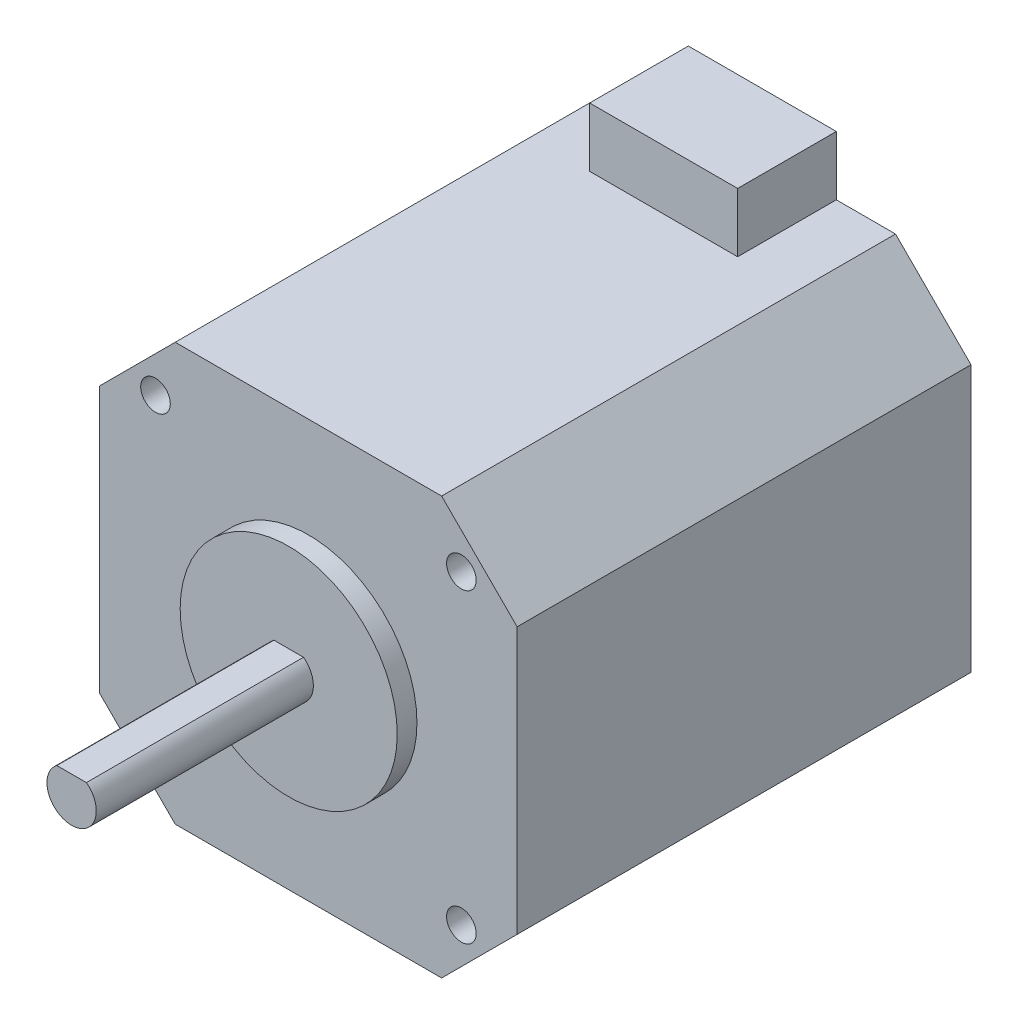
SolidWorks part; units mm, degrees
ref_plane "Front Plane" through (0, 0, 0) normal (0, 0, 1) x (1, 0, 0)
ref_plane "Top Plane" through (0, 0, 0) normal (0, 1, 0) x (1, 0, 0)
ref_plane "Right Plane" through (0, 0, 0) normal (1, 0, 0) x (0, 0, -1)
sketch "Sketch1" plane through (0, 0, 0) normal (0, 0, 1) x (1, 0, 0)
  line L0 (7.65, 0) -> (0, 7.65)
  line L1 (0, 7.65) -> (0, 34.65)
  line L2 (0, 34.65) -> (7.65, 42.3)
  line L3 (7.65, 42.3) -> (34.65, 42.3)
  line L4 (34.65, 42.3) -> (42.3, 34.65)
  line L5 (42.3, 34.65) -> (42.3, 7.65)
  line L6 (42.3, 7.65) -> (34.65, 0)
  line L7 (34.65, 0) -> (7.65, 0)
  dimension "D1" = 7.65
  dimension "D2" = 7.65
  dimension "D3" = 27
  dimension "D4" = 7.65
  dimension "D5" = 27
  dimension "D6" = 27
  dimension "D7" = 7.65
  dimension "D8" = 7.65
extrude "Boss-Extrude1" add sketch "Sketch1" along normal blind 46
sketch "Sketch3" plane through (0, 0, 46) normal (0, 0, 1) x (1, 0, 0)
  circle A0 centre (21.15, 21.15) radius 11
  point P0 (0, 0)
  dimension "D1" = 22
extrude "Boss-Extrude2" add sketch "Sketch3" along normal blind 2
sketch "Sketch4" plane through (0, 0, 48) normal (0, 0, 1) x (1, 0, 0)
  circle A0 centre (21.15, 21.15) radius 2.5
  dimension "D1" = 5
extrude "Boss-Extrude3" add sketch "Sketch4" along normal blind 22
sketch "Sketch5" plane through (0, 0, 70) normal (0, 0, 1) x (1, 0, 0)
  line L1 (21.15, 23.15) -> (22.65, 23.15)
  line L2 (21.15, 23.15) -> (19.65, 23.15)
  arc A2 (22.65, 23.15) -> (19.65, 23.15) centre (21.15, 21.15) ccw
extrude "Cut-Extrude1" cut sketch "Sketch5" against normal blind 22
sketch "Sketch6" plane through (0, 0, 46) normal (0, 0, 1) x (1, 0, 0)
  circle A0 centre (5.65, 5.65) radius 1.5
  circle A1 centre (5.65, 36.65) radius 1.5
  circle A2 centre (36.65, 5.65) radius 1.5
  circle A3 centre (36.65, 36.65) radius 1.5
  point P4 (0, 0)
  point P7 (0, 0)
  point P8 (0, 0)
  dimension "D1" = 3
  dimension "D3" = 3
  dimension "D2" = 3
extrude "Cut-Extrude2" cut sketch "Sketch6" against normal blind 4.5
sketch "Sketch7" plane through (0, 42.3, 0) normal (0, 1, 0) x (1, 0, 0)
  line L1 (34.65, 0) -> (7.65, 0) construction
  line L3 (13.65, 0) -> (28.65, 0)
  line L4 (13.65, 0) -> (13.65, -10)
  line L5 (13.65, -10) -> (28.65, -10)
  line L6 (28.65, 0) -> (28.65, -10)
  dimension "D2" = 15
  dimension "D3" = 10
extrude "Boss-Extrude4" add sketch "Sketch7" along normal blind 6
